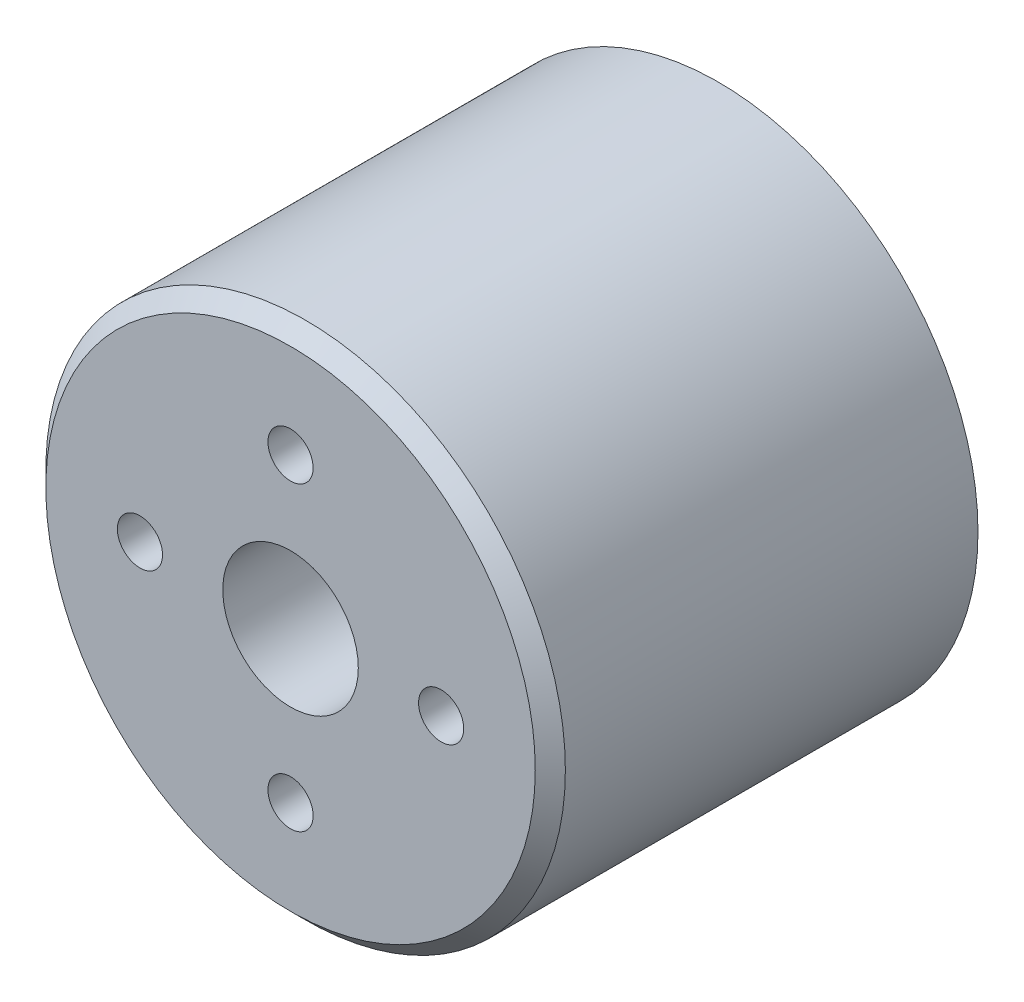
SolidWorks part; units mm, degrees
ref_plane "Plan de face" through (0, 0, 0) normal (0, 0, 1) x (1, 0, 0)
ref_plane "Plan de dessus" through (0, 0, 0) normal (0, 1, 0) x (1, 0, 0)
ref_plane "Plan de droite" through (0, 0, 0) normal (1, 0, 0) x (0, 0, -1)
sketch "Esquisse1" plane through (0, 0, 0) normal (0, 0, 1) x (1, 0, 0)
  circle A0 centre (0, 0) radius 17.25
  dimension "D1" = 34.5
extrude "Boss.-Extru.1" add sketch "Esquisse1" along normal blind 28.4
chamfer "Chanfrein1" distance 1 angle 45 1 edges at (17.25, 0, 28.4)
sketch "Esquisse2" plane through (0, 0, 0) normal (0, 0, -1) x (-1, 0, 0)
  line L0 (8.6603, 5) -> (-8.6603, 5) construction
  line L1 (-8.6603, 5) -> (0, -10) construction
  line L2 (0, -10) -> (8.6603, 5) construction
  line L3 (7.7132, 13.3597) -> (7.7132, -13.3597) construction
  line L4 (7.7132, -13.3597) -> (-15.4264, 0) construction
  line L5 (-15.4264, 0) -> (7.7132, 13.3597) construction
  line L6 (0, -10) -> (0, 0) construction
  line L7 (-15.4264, 0) -> (0, 0) construction
  circle A0 centre (0, 0) radius 15.4264 construction
  circle A1 centre (0, 0) radius 10 construction
  circle A4 centre (8.6603, 5) radius 1.5
  circle A5 centre (0, -10) radius 1.5
  circle A6 centre (-8.6603, 5) radius 1.5
  circle A8 centre (7.7132, 13.3597) radius 1.25
  circle A9 centre (7.7132, -13.3597) radius 1.25
  circle A10 centre (-15.4264, 0) radius 1.25
  dimension "D1" = 2.5
  dimension "D2" = 20
  dimension "D3" = 3
extrude "Enlèv. mat.-Extru.1" cut sketch "Esquisse2" against normal blind 3
sketch "Esquisse3" plane through (0, 0, 28.4) normal (0, 0, 1) x (1, 0, 0)
  line L0 (-10, 0) -> (0, 10) construction
  line L1 (0, 10) -> (10, 0) construction
  line L2 (10, 0) -> (0, -10) construction
  line L3 (0, -10) -> (-10, 0) construction
  circle A0 centre (0, 0) radius 10 construction
  circle A1 centre (0, 10) radius 1.5
  circle A2 centre (10, 0) radius 1.5
  circle A3 centre (0, -10) radius 1.5
  circle A4 centre (-10, 0) radius 1.5
  dimension "D1" = 3
  dimension "D2" = 20
extrude "Enlèv. mat.-Extru.2" cut sketch "Esquisse3" against normal blind 2.5
sketch "Esquisse4" plane through (0, 0, 28.4) normal (0, 0, 1) x (1, 0, 0)
  circle A0 centre (0, 0) radius 4.5
  dimension "D1" = 9
extrude "Enlèv. mat.-Extru.4" cut sketch "Esquisse4" against normal through all
